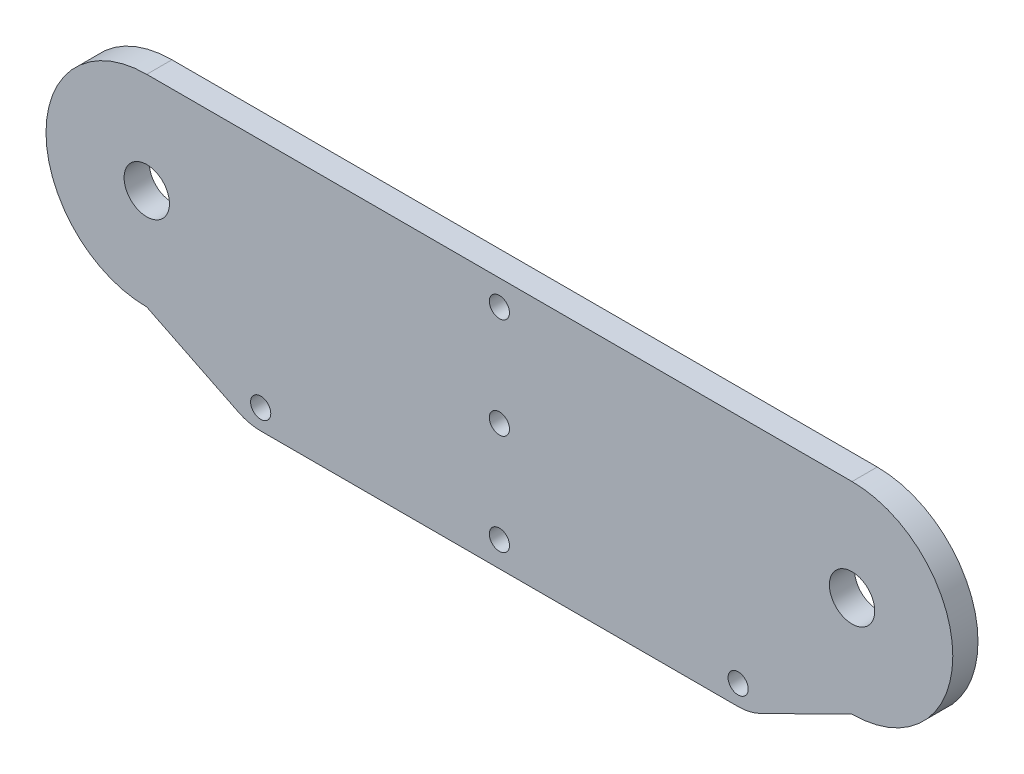
SolidWorks part; units mm, degrees
ref_plane "前视基准面" through (0, 0, 0) normal (0, 0, 1) x (1, 0, 0)
ref_plane "上视基准面" through (0, 0, 0) normal (0, 1, 0) x (1, 0, 0)
ref_plane "右视基准面" through (0, 0, 0) normal (1, 0, 0) x (0, 0, -1)
other "Configuration Table"
sketch "草图1" plane through (0, 0, 0) normal (0, 0, 1) x (1, 0, 0)
  line L0 (0, 20) -> (140, 20)
  line L1 (0, 20) -> (0, -20)
  line L2 (70, -1000) -> (70, 49000) construction
  line L3 (70, 20) -> (70, -30)
  line L4 (0, -20) -> (18.1933, -28.9693)
  line L5 (22.6151, -30) -> (117.3849, -30)
  line L6 (140, -20) -> (121.8067, -28.9693)
  line L7 (70, 20) -> (70, 15)
  line L8 (70, -30) -> (70, -25)
  line L9 (140, 20) -> (140, -20)
  circle A0 centre (0, 0) radius 4.5
  circle A1 centre (0, 0) radius 20
  circle A2 centre (140, 0) radius 20
  circle A3 centre (140, 0) radius 4.5
  circle A4 centre (70, 15) radius 2
  circle A5 centre (70, -25) radius 2
  circle A6 centre (70, -5) radius 2
  arc A7 (117.3849, -30) -> (121.8067, -28.9693) centre (117.3849, -20) ccw
  arc A8 (22.6151, -30) -> (18.1933, -28.9693) centre (22.6151, -20) cw
  point P25 (119.7159, -30)
  point P28 (20.2841, -30)
  dimension "D1" = 9
  dimension "D3" = 40
  dimension "D4" = 50
  dimension "D6" = 4
  dimension "D8" = 4
  dimension "D9" = 4
  dimension "D10" = 10
  dimension "D2" = 140
  dimension "D5" = 5
  dimension "D7" = 5
extrude "凸台-拉伸1" add sketch "草图1" along normal blind 5 contours L1 A1 A0 | L1 A1 A0 | A8 L5 L8 A5 L3 A6 A4 L0 A1 L4 | L5 A7 L6 A2 L0 L3 A4 A6 A5 L8 | L9 A3 A2 | L9 A3 A2
sketch "草图2" plane through (0, 0, 5) normal (0, 0, 1) x (1, 0, 0)
  line L0 (22.6151, -30) -> (22.6151, -26)
  line L1 (117.3849, -30) -> (117.3849, -26)
  circle A0 centre (22.6151, -26) radius 2
  circle A1 centre (117.3849, -26) radius 2
  dimension "D2" = 4
  dimension "D4" = 4
  dimension "D1" = 4
  dimension "D3" = 4
extrude "切除-拉伸1" cut sketch "草图2" against normal blind 5 contours A0 | A1
